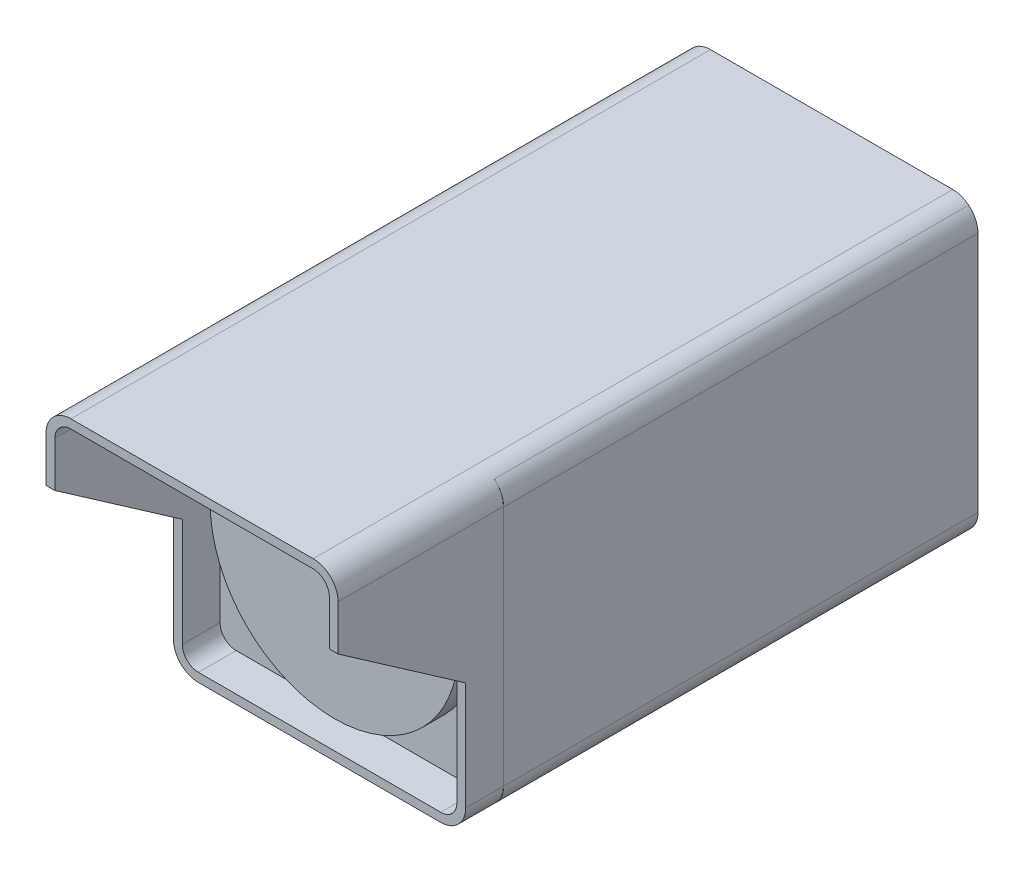
SolidWorks part; units mm, degrees
ref_plane "Front Plane" through (0, 0, 0) normal (0, 0, 1) x (1, 0, 0)
ref_plane "Top Plane" through (0, 0, 0) normal (0, 1, 0) x (1, 0, 0)
ref_plane "Right Plane" through (0, 0, 0) normal (1, 0, 0) x (0, 0, -1)
sketch "Sketch2" plane through (0, 0, 0) normal (0, 0, 1) x (1, 0, 0)
  line L0 (1458.2207, 1652.2207) -> (-1458.2207, 1652.2207)
  line L1 (1458.2207, -1758.2207) -> (-1458.2207, -1758.2207)
  line L2 (1758.2207, -1458.2207) -> (1758.2207, 1458.2207)
  line L3 (1458.2207, 1758.2207) -> (-1458.2207, 1758.2207)
  line L4 (-1758.2207, -1458.2207) -> (-1758.2207, 1458.2207)
  line L7 (-1652.2207, -1458.2207) -> (-1652.2207, 1458.2207)
  line L8 (1458.2207, -1652.2207) -> (-1458.2207, -1652.2207)
  line L9 (1652.2207, -1458.2207) -> (1652.2207, 1458.2207)
  line L11 (-1670.3527, 1670.3527) -> (-1758.2207, 1758.2207) construction
  arc A0 (1458.2207, -1758.2207) -> (1758.2207, -1458.2207) centre (1458.2207, -1458.2207) ccw
  arc A1 (1758.2207, 1458.2207) -> (1458.2207, 1758.2207) centre (1458.2207, 1458.2207) ccw
  arc A2 (-1458.2207, -1758.2207) -> (-1758.2207, -1458.2207) centre (-1458.2207, -1458.2207) cw
  arc A3 (-1458.2207, 1758.2207) -> (-1758.2207, 1458.2207) centre (-1458.2207, 1458.2207) ccw
  arc A4 (-1458.2207, 1652.2207) -> (-1652.2207, 1458.2207) centre (-1458.2207, 1458.2207) ccw
  arc A5 (-1458.2207, -1652.2207) -> (-1652.2207, -1458.2207) centre (-1458.2207, -1458.2207) cw
  arc A6 (1458.2207, -1652.2207) -> (1652.2207, -1458.2207) centre (1458.2207, -1458.2207) ccw
  arc A7 (1652.2207, 1458.2207) -> (1458.2207, 1652.2207) centre (1458.2207, 1458.2207) ccw
  point P0 (0, 0)
extrude "Boss-Extrude1" add sketch "Sketch2" along normal blind 7698 contours L0 A4 L7 A5 L8 A6 L9 A7 | A3 L3 A1 L2 A0 L1 A2 L4
sketch "Sketch3" plane through (0, 0, 0) normal (0, 0, -1) x (-1, 0, 0)
  line L1 (1462.2666, -1754.9479) -> (-1462.2666, -1754.9479)
  line L2 (1762.2666, -1454.9479) -> (1762.2666, 1454.9479)
  line L3 (1462.2666, 1754.9479) -> (-1462.2666, 1754.9479)
  line L4 (-1762.2666, -1454.9479) -> (-1762.2666, 1454.9479)
  line L5 (1762.2666, -1754.9479) -> (-1762.2666, 1754.9479) construction
  line L6 (1762.2666, 1754.9479) -> (-1762.2666, -1754.9479) construction
  arc A0 (-1462.2666, -1754.9479) -> (-1762.2666, -1454.9479) centre (-1462.2666, -1454.9479) cw
  arc A1 (1462.2666, -1754.9479) -> (1762.2666, -1454.9479) centre (1462.2666, -1454.9479) ccw
  arc A2 (1762.2666, 1454.9479) -> (1462.2666, 1754.9479) centre (1462.2666, 1454.9479) ccw
  arc A3 (-1462.2666, 1754.9479) -> (-1762.2666, 1454.9479) centre (-1462.2666, 1454.9479) ccw
  point P0 (0, 0)
  dimension "D1" = 300
extrude "Boss-Extrude2" add sketch "Sketch3" against normal blind 5709
sketch "Sketch4" plane through (1758.2207, 0, 0) normal (1, 0, 0) x (0, 0, -1)
  line L0 (-7698, 914.4491) -> (-7698, -1758.2207)
  line L1 (-7698, -1458.2207) -> (-7698, 1458.2207) construction
  line L2 (-7698, -1758.2207) -> (-6163.0898, -1758.2207)
  line L3 (-7698, -1758.2207) -> (0, -1758.2207) construction
  line L4 (-6163.0898, -1758.2207) -> (-6163.0898, -153.9798)
  line L5 (-6163.0898, -153.9798) -> (-7698, 914.4491)
extrude "Cut-Extrude1" cut sketch "Sketch4" against normal blind 5709
sketch "Sketch5" plane through (0, -1758.2207, 0) normal (0, -1, 0) x (1, 0, 0)
  circle A0 centre (0, 1152.4011) radius 688.9219
  circle A1 centre (0, 1152.4011) radius 500
extrude "Boss-Extrude3" add sketch "Sketch5" along normal blind 102
sketch "Sketch7" plane through (0, 0, 5709) normal (0, 0, 1) x (1, 0, 0)
  circle A0 centre (0, 0) radius 1495.8689
extrude "Boss-Extrude4" add sketch "Sketch7" along normal blind 275
